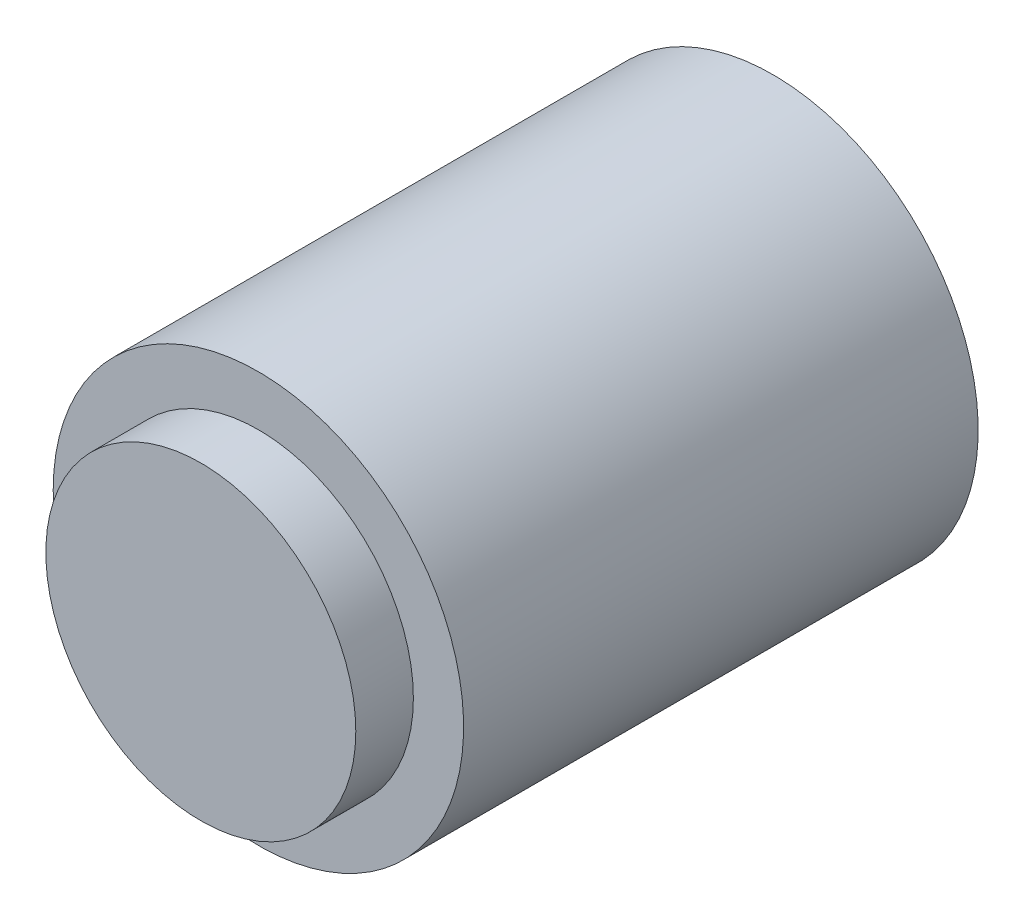
SolidWorks part; units mm, degrees
material "Rubber"
ref_plane "Front Plane" through (0, 0, 0) normal (0, 0, 1) x (1, 0, 0)
ref_plane "Top Plane" through (0, 0, 0) normal (0, 1, 0) x (1, 0, 0)
ref_plane "Right Plane" through (0, 0, 0) normal (1, 0, 0) x (0, 0, -1)
sketch "Sketch1" plane through (0, 0, 0) normal (0, 0, 1) x (1, 0, 0)
  circle A0 centre (0, 0) radius 16.75
  dimension "D1" = 33.5
extrude "Boss-Extrude1" add sketch "Sketch1" along normal blind 42
sketch "Sketch2" plane through (0, 0, 42) normal (0, 0, 1) x (1, 0, 0)
  circle A0 centre (0, 0) radius 12.65
  dimension "D1" = 25.3
extrude "Boss-Extrude2" add sketch "Sketch2" along normal blind 4.7
sketch "Sketch3" plane through (0, 0, 0) normal (0, 0, -1) x (-1, 0, 0)
  circle A0 centre (0, 0) radius 15.5
  dimension "D1" = 31
extrude "Cut-Extrude1" cut sketch "Sketch3" against normal blind 4.7
